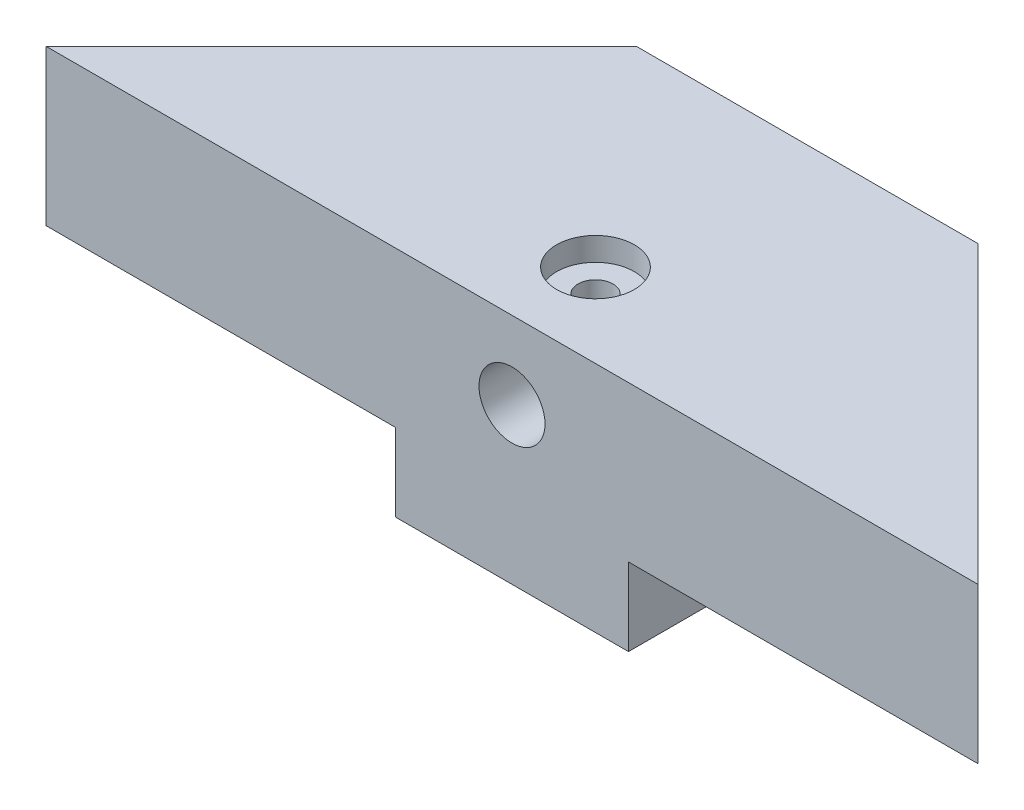
SolidWorks part; units mm, degrees
ref_plane "Front Plane" through (0, 0, 0) normal (0, 0, 1) x (1, 0, 0)
ref_plane "Top Plane" through (0, 0, 0) normal (0, 1, 0) x (1, 0, 0)
ref_plane "Right Plane" through (0, 0, 0) normal (1, 0, 0) x (0, 0, -1)
sketch "Sketch1" plane through (0, 0, 0) normal (0, 1, 0) x (1, 0, 0)
  line L0 (0, 0) -> (60, 0)
  line L1 (0, 0) -> (-60, 0)
  line L3 (0, 38) -> (22, 38)
  line L4 (0, 38) -> (-22, 38)
  line L5 (-60, 0) -> (-22, 38)
  line L6 (22, 38) -> (60, 0)
  dimension "D1" = 60
  dimension "D2" = 60
  dimension "D3" = 38
  dimension "D4" = 22
  dimension "D5" = 22
extrude "Boss-Extrude1" add sketch "Sketch1" along normal blind 20
sketch "Sketch2" plane through (0, 20, 0) normal (0, 1, 0) x (1, 0, 0)
  circle A0 centre (0, 10.75) radius 5
  dimension "D2" = 10
extrude "Cut-Extrude1" cut sketch "Sketch2" along direction (0, -1, 0) on the side against the normal blind 3
sketch "Sketch3" plane through (0, 20, 0) normal (0, 1, 0) x (1, 0, 0)
  circle A0 centre (0, 10.75) radius 2.25
  dimension "D2" = 4.5
extrude "Cut-Extrude2" cut sketch "Sketch3" along direction (0, -1, 0) on the side against the normal blind 10
sketch "Sketch4" plane through (0, 0, 0) normal (0, 0, 1) x (1, 0, 0)
  circle A0 centre (0, 10) radius 4.25
  dimension "8.5" = 8.5
extrude "Cut-Extrude3" cut sketch "Sketch4" along direction (0, 0, -1) on the side against the normal blind 20
sketch "Sketch5" plane through (0, 0, 0) normal (0, -1, 0) x (1, 0, 0)
  line L1 (-60, 0) -> (60, 0) construction
  line L3 (-15, 0) -> (-15, -25)
  line L4 (15, 0) -> (15, -25)
  line L5 (-15, -25) -> (-14.3927, -25.4183)
  line L6 (-15, -25) -> (15, -25)
  line M5 (60, 0) -> (-60, 0)
  dimension "D3" = 25
  dimension "D4" = 25
extrude "Boss-Extrude2" add sketch "Sketch5" along direction (0, -1, 0) on the side of the normal blind 10 contours L3 L6 L4 M5
sketch "Sketch6" plane through (0, -10, 0) normal (0, -1, 0) x (1, 0, 0)
  line L0 (15, 0) -> (15, -12.5)
  line L1 (15, 0) -> (15, -25) construction
  circle A0 centre (-7.5, -12.5) radius 2.25
  circle A1 centre (7.5, -12.5) radius 2.25
  dimension "D4" = 4.5
  dimension "D2" = 15
  dimension "D3" = 4.5
  dimension "D1" = 12.5
extrude "Cut-Extrude7" cut sketch "Sketch6" along direction (0, -1, 0) on the side against the normal blind 10 contours A0 | A1
